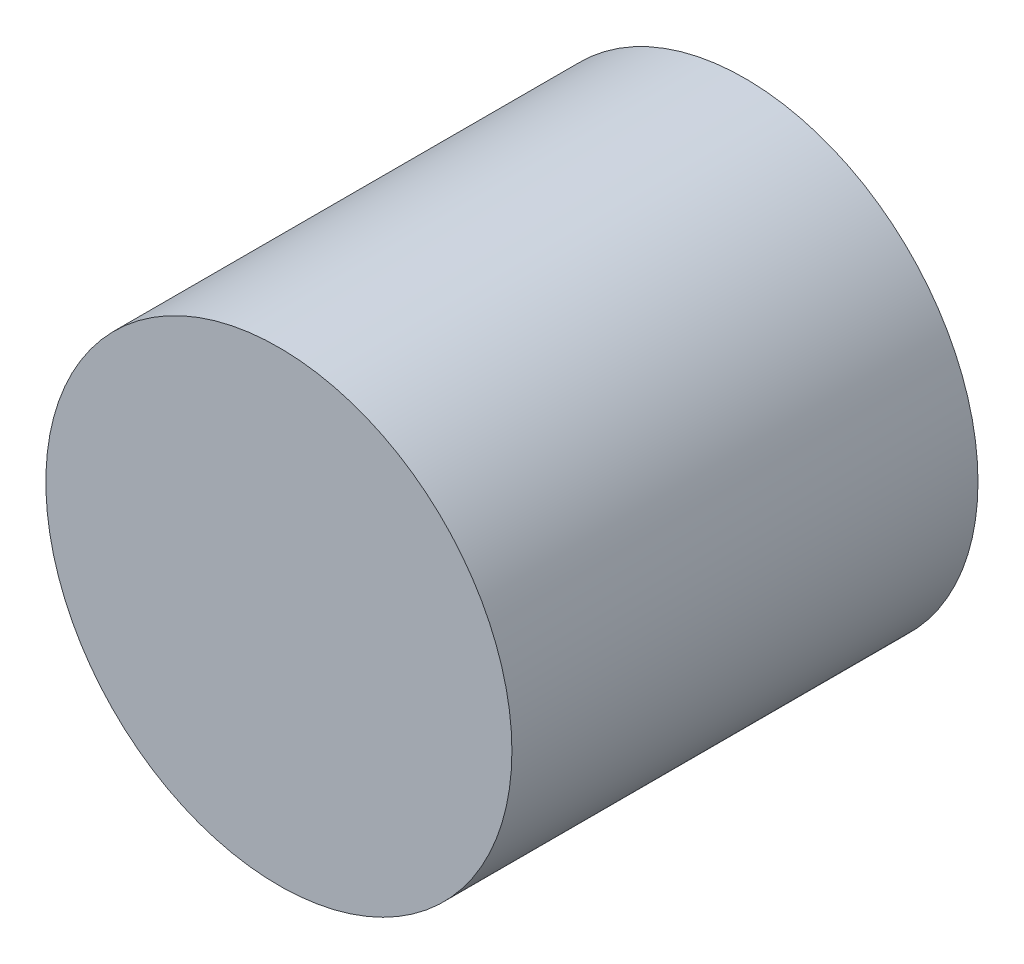
SolidWorks part; units mm, degrees
ref_plane "Спереди" through (0, 0, 0) normal (0, 0, 1) x (1, 0, 0)
ref_plane "Сверху" through (0, 0, 0) normal (0, 1, 0) x (1, 0, 0)
ref_plane "Справа" through (0, 0, 0) normal (1, 0, 0) x (0, 0, -1)
sketch "Эскиз1" plane through (0, 0, 0) normal (0, 0, 1) x (1, 0, 0)
  circle A0 centre (0, 0) radius 0.5
  dimension "D1" = 1
extrude "Бобышка-Вытянуть1" add sketch "Эскиз1" along normal blind 1
